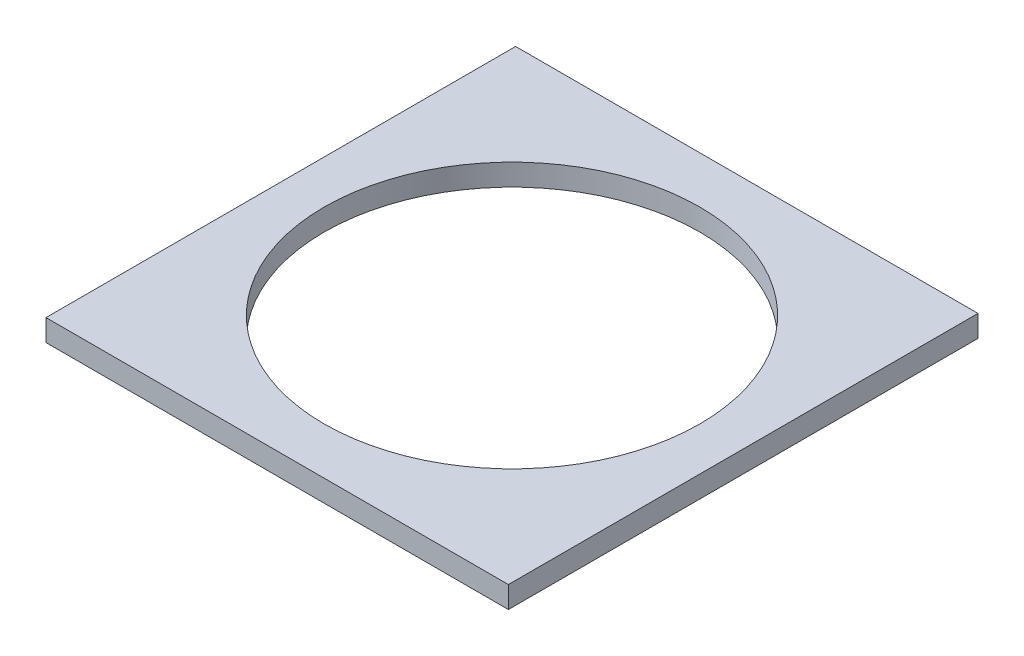
SolidWorks part; units mm, degrees
ref_plane "Front Plane" through (0, 0, 0) normal (0, 0, 1) x (1, 0, 0)
ref_plane "Top Plane" through (0, 0, 0) normal (0, 1, 0) x (1, 0, 0)
ref_plane "Right Plane" through (0, 0, 0) normal (1, 0, 0) x (0, 0, -1)
sketch "Sketch4" plane through (0, 0, 0) normal (0, 1, 0) x (1, 0, 0)
  line L0 (-58.6759, -30.6872) -> (5.3241, -30.6872)
  line L1 (5.3241, -30.6872) -> (5.3241, 34.3128)
  line L2 (5.3241, 34.3128) -> (-58.6759, 34.3128)
  line L3 (-58.6759, 34.3128) -> (-58.6759, -30.6872)
  circle A0 centre (-26.6759, 1.8128) radius 26
  dimension "D3" = 52
  dimension "D1" = 64
  dimension "D2" = 65
  dimension "D4" = 32
  dimension "D5" = 32.5
  dimension "D6" = 34.3128
  dimension "D7" = 5.3241
extrude "Boss-Extrude2" add sketch "Sketch4" along normal blind 3
